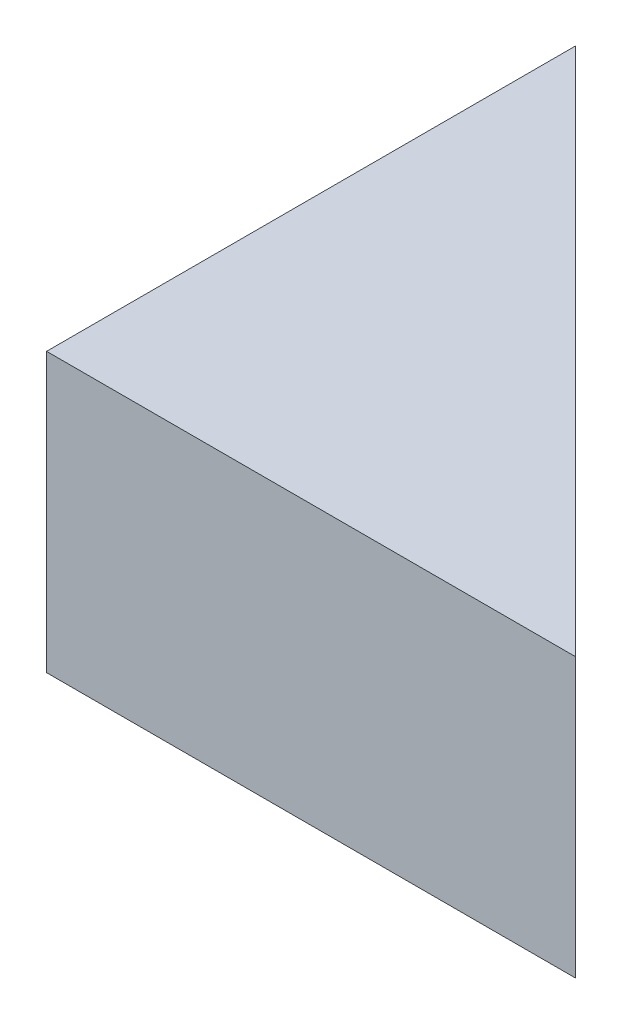
SolidWorks part; units mm, degrees
ref_plane "Front Plane" through (0, 0, 0) normal (0, 0, 1) x (1, 0, 0)
ref_plane "Top Plane" through (0, 0, 0) normal (0, 1, 0) x (1, 0, 0)
ref_plane "Right Plane" through (0, 0, 0) normal (1, 0, 0) x (0, 0, -1)
sketch "Sketch2" plane through (0, 0, 0) normal (0, 1, 0) x (1, 0, 0)
  line L1 (19, -19) -> (-19, -19)
  line L2 (19, -19) -> (19, 19)
  line L3 (19, 19) -> (-19, 19)
  line L4 (-19, -19) -> (-19, 19)
  line L5 (19, -19) -> (-19, 19) construction
  line L6 (19, 19) -> (-19, -19) construction
  point P0 (0, 0)
  dimension "D1" = 38
  dimension "D2" = 38
extrude "Boss-Extrude1" add sketch "Sketch2" along normal blind 20
sketch "Sketch3" plane through (0, 20, 0) normal (0, 1, 0) x (1, 0, 0)
  line L0 (-19, 19) -> (19, -19)
  line L1 (19, -19) -> (19, 19)
  line L2 (19, 19) -> (-19, 19)
extrude "Cut-Extrude1" cut sketch "Sketch3" against normal blind 20
sketch "Sketch7" plane through (0, 0, 0) normal (0, -1, 0) x (-1, 0, 0)
  line L0 (19, 0) -> (12.5, 0)
  line L1 (19, 19) -> (19, 0) construction
  line L2 (0, -19) -> (0, -12.5)
  line L3 (19, -19) -> (-19, -19) construction
  circle A0 centre (12.5, 0) radius 2.25
  circle A1 centre (0, -12.5) radius 2.25
  dimension "D3" = 4.5
  dimension "D4" = 4.5
  dimension "D1" = 6.5
  dimension "D2" = 6.5
extrude "Cut-Extrude2" cut sketch "Sketch7" against normal blind 5
